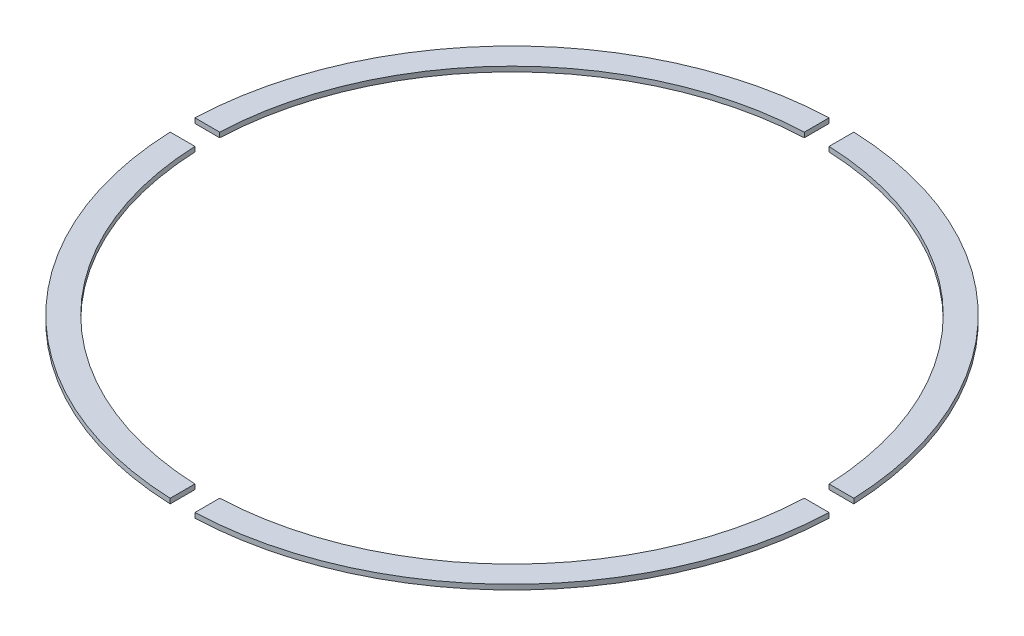
SolidWorks part; units mm, degrees
ref_plane "Front Plane" through (0, 0, 0) normal (0, 0, 1) x (1, 0, 0)
ref_plane "Top Plane" through (0, 0, 0) normal (0, 1, 0) x (1, 0, 0)
ref_plane "Right Plane" through (0, 0, 0) normal (1, 0, 0) x (0, 0, -1)
sketch "Sketch1" plane through (0, 0, 0) normal (0, 1, 0) x (1, 0, 0)
  line L0 (185, 0) -> (-185, 0) construction
  circle A0 centre (0, 0) radius 185
  circle A1 centre (0, 0) radius 200
  dimension "D1" = 370
  dimension "D2" = 400
extrude "Boss-Extrude1" add sketch "Sketch1" along normal mid plane 3
sketch "Sketch3" plane through (0, 0, 0) normal (0, 0, 1) x (1, 0, 0)
  line L0 (0, 143.41) -> (0, -149.1546) construction
sketch "Sketch2" plane through (0, 0, 0) normal (0, 1, 0) x (1, 0, 0)
  line L1 (157.6447, 7.5) -> (227.3553, 7.5)
  line L2 (157.6447, 7.5) -> (157.6447, -7.5)
  line L3 (157.6447, -7.5) -> (227.3553, -7.5)
  line L4 (227.3553, 7.5) -> (227.3553, -7.5)
  line L5 (157.6447, 7.5) -> (227.3553, -7.5) construction
  line L6 (157.6447, -7.5) -> (227.3553, 7.5) construction
  circle A0 centre (0, 0) radius 192.5 construction
  circle A1 centre (0, 0) radius 185 construction
  point P5 (192.5, 0)
  point P10 (227.3553, 10)
  point P11 (192.5, 0)
  dimension "D1" = 7.5
  dimension "D2" = 15
extrude "Cut-Extrude1" cut sketch "Sketch2" against normal through all and the other way through all
pattern_circular "CirPattern1" count 4 every 90 about axis through (0, 0, 0) along (0, 1, 0) of "Cut-Extrude1"
